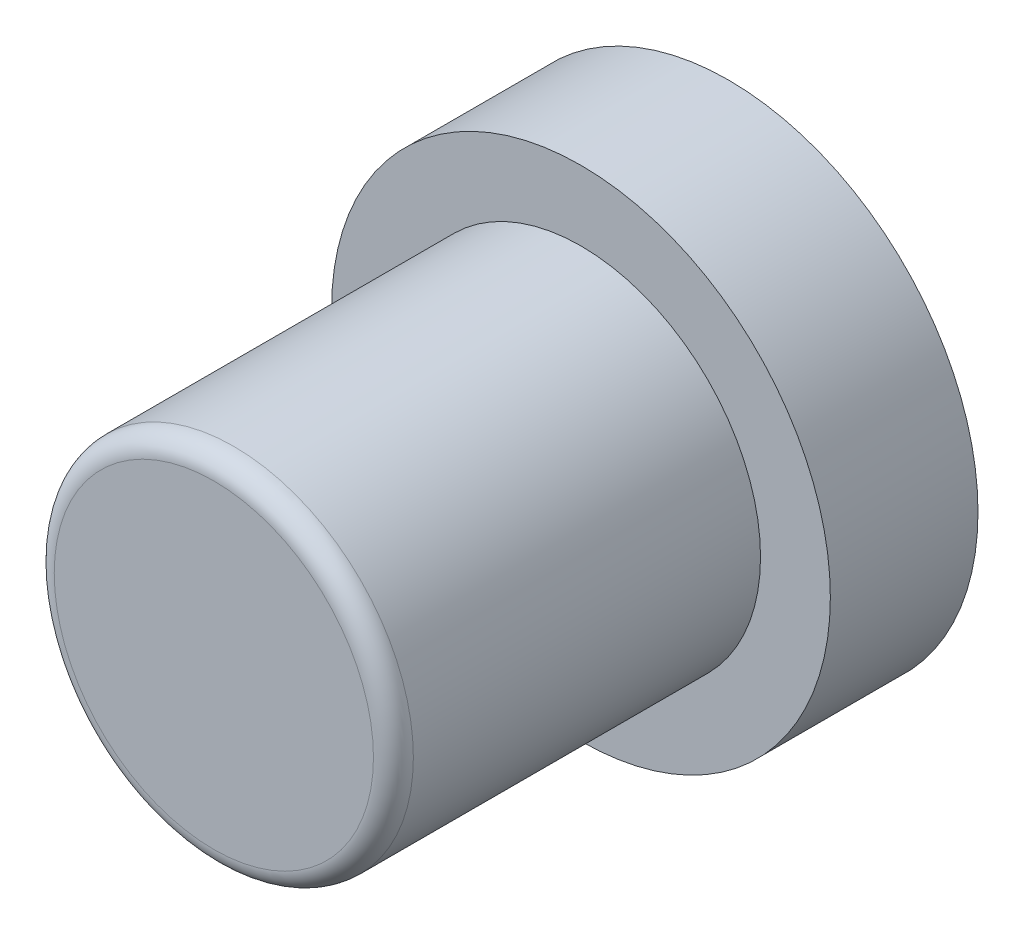
SolidWorks part; units mm, degrees
ref_plane "Front Plane" through (0, 0, 0) normal (0, 0, 1) x (1, 0, 0)
ref_plane "Top Plane" through (0, 0, 0) normal (0, 1, 0) x (1, 0, 0)
ref_plane "Right Plane" through (0, 0, 0) normal (1, 0, 0) x (0, 0, -1)
sketch "Sketch1" plane through (0, 0, 0) normal (0, 0, 1) x (1, 0, 0)
  circle A0 centre (0, 0) radius 6.25
  dimension "D1" = 12.5
extrude "Boss-Extrude1" add sketch "Sketch1" along normal blind 3.7
sketch "Sketch2" plane through (0, 0, 3.7) normal (0, 0, 1) x (1, 0, 0)
  circle A0 centre (0, 0) radius 4.5
  dimension "D1" = 9
extrude "Boss-Extrude2" add sketch "Sketch2" along normal blind 9.2
fillet "Fillet1" radius 0.5 1 edges at (4.5, 0, 12.9)
equation "\"D1@Boss-Extrude2\"=4.2+5"
